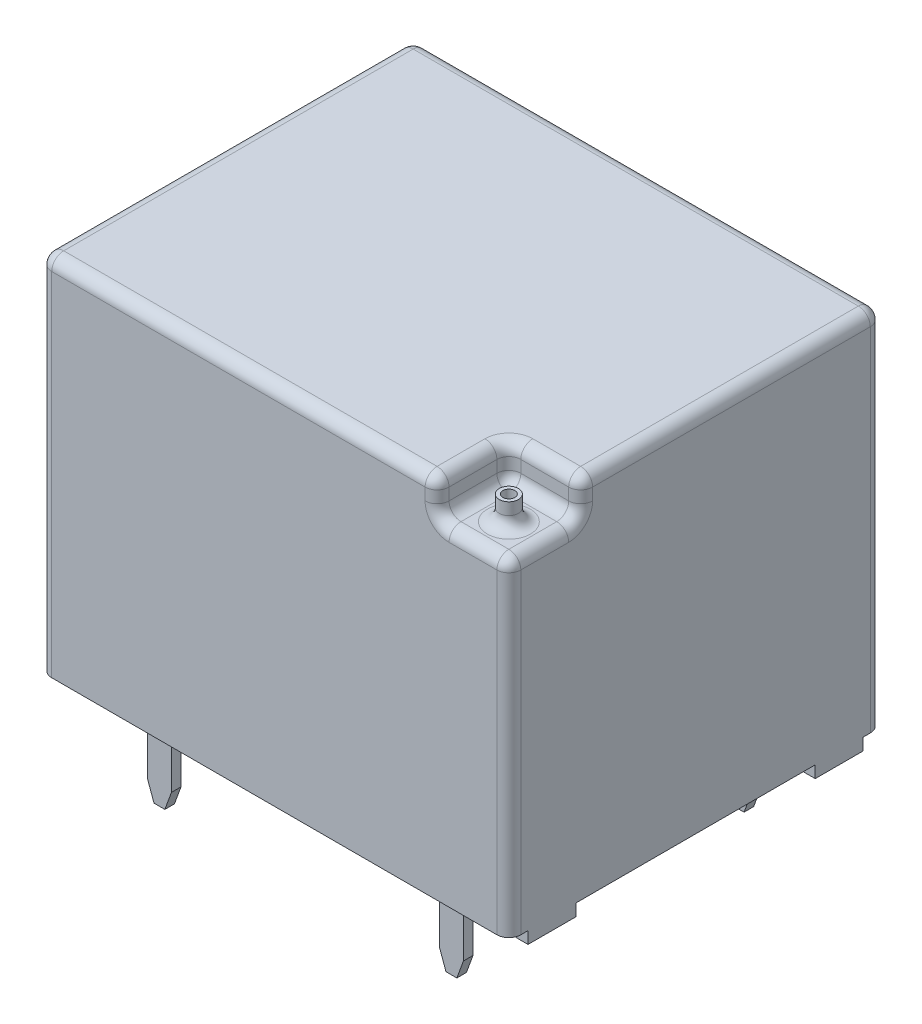
SolidWorks part; units mm, degrees
ref_plane "Спереди" through (0, 0, 0) normal (0, 0, 1) x (1, 0, 0)
ref_plane "Сверху" through (0, 0, 0) normal (0, 1, 0) x (1, 0, 0)
ref_plane "Справа" through (0, 0, 0) normal (1, 0, 0) x (0, 0, -1)
sketch "Эскиз1" plane through (0, 0, 0) normal (0, 1, 0) x (1, 0, 0)
  line L1 (-9.8, -7.8) -> (9.8, -7.8)
  line L2 (-9.8, -7.8) -> (-9.8, 7.8)
  line L3 (-9.8, 7.8) -> (9.8, 7.8)
  line L4 (9.8, -7.8) -> (9.8, 7.8)
  line L5 (-9.8, -7.8) -> (9.8, 7.8) construction
  line L6 (-9.8, 7.8) -> (9.8, -7.8) construction
  point P0 (0, 0)
  dimension "D1" = 19.6
  dimension "D2" = 15.6
extrude "Бобышка-Вытянуть1" add sketch "Эскиз1" along normal blind 15.2
sketch "Эскиз2" plane through (0, 15.2, 0) normal (0, 1, 0) x (1, 0, 0)
  line L0 (9.8, -7.8) -> (9.8, 7.8) construction
  line L1 (9.8, -7.8) -> (6.8, -7.8)
  line L2 (9.8, -7.8) -> (9.8, -4.8)
  line L3 (9.8, -4.8) -> (6.8, -4.8)
  line L4 (6.8, -7.8) -> (6.8, -4.8)
  dimension "D1" = 3
extrude "Вырез-Вытянуть1" cut sketch "Эскиз2" against normal blind 1.5
sketch "Эскиз3" plane through (0, 13.7, 0) normal (0, 1, 0) x (1, 0, 0)
  line L0 (6.8, -7.8) -> (9.8, -7.8) construction
  line L1 (9.8, -7.8) -> (9.8, -4.8) construction
  circle A0 centre (8.3, -6.3) radius 0.4
  circle A1 centre (8.3, -6.3) radius 0.25
  point P3 (8.3, -7.8)
  point P4 (9.8, -6.3)
  dimension "D1" = 0.8
  dimension "D2" = 0.5
extrude "Бобышка-Вытянуть2" add sketch "Эскиз3" along normal blind 1
sketch "Эскиз5" plane through (0, 0, 0) normal (0, -1, 0) x (1, 0, 0)
  line L0 (-12.3482, 0) -> (15.0371, 0) construction
  line L2 (-9.55, -6) -> (-9.55, 6) construction
  line L3 (-9.3, 5) -> (-9.8, 5)
  line L4 (-9.3, 5) -> (-9.3, 7)
  line L5 (-9.3, 7) -> (-9.8, 7)
  line L6 (-9.8, 5) -> (-9.8, 7)
  line L7 (-9.3, 5) -> (-9.8, 7) construction
  line L9 (-9.3, 7) -> (-9.8, 5) construction
  line L10 (-9.3, -7) -> (-9.8, -7)
  line L11 (-9.3, -7) -> (-9.3, -5)
  line L12 (-9.3, -5) -> (-9.8, -5)
  line L13 (-9.8, -7) -> (-9.8, -5)
  line L14 (-9.3, -7) -> (-9.8, -5) construction
  line L15 (-9.3, -5) -> (-9.8, -7) construction
  line L16 (9.8, -7) -> (9.3, -7)
  line L17 (9.8, -7) -> (9.8, -5)
  line L18 (9.8, -5) -> (9.3, -5)
  line L19 (9.3, -7) -> (9.3, -5)
  line L20 (9.8, -7) -> (9.3, -5) construction
  line L21 (9.8, -5) -> (9.3, -7) construction
  line L22 (9.8, 5) -> (9.3, 5)
  line L23 (9.8, 5) -> (9.8, 7)
  line L24 (9.8, 7) -> (9.3, 7)
  line L25 (9.3, 5) -> (9.3, 7)
  line L26 (9.8, 5) -> (9.3, 7) construction
  line L27 (9.8, 7) -> (9.3, 5) construction
  line L28 (-9.8, -7.8) -> (-9.8, 7.8) construction
  line L29 (9.8, 7.8) -> (9.8, -7.8) construction
  point P1 (-9.55, 6)
  point P8 (-9.55, -6)
  point P13 (9.55, -6)
  point P18 (9.55, 6)
  point P26 (-9.55, 0)
  dimension "D1" = 2
  dimension "D2" = 0.5
  dimension "D3" = 12
extrude "Бобышка-Вытянуть4" add sketch "Эскиз5" along normal blind 0.5
fillet "Скругление1" radius 0.5 18 edges at (8.3, 15.2, 4.8) (-9.8, 7.6, -7.8) (-9.8, 15.2, 0) (9.8, 7.6, -7.8) (0, 15.2, -7.8) (9.8, 15.2, -1.5) (8.3, 13.7, 6.7) (6.8, 13.7, 6.3) (8.3, 13.7, 4.8) (9.8, 14.45, 4.8) (8.3, 13.7, 7.8) (9.8, 13.7, 6.3) (6.8, 14.45, 4.8) (6.8, 15.2, 6.3) (6.8, 14.45, 7.8) (-1.5, 15.2, 7.8) (9.8, 6.85, 7.8) (-9.8, 7.6, 7.8)
sketch "Эскиз4" plane through (0, 0, 0) normal (0, -1, 0) x (1, 0, 0)
  line L0 (-11.9961, 0) -> (11.2464, 0) construction
  line L1 (9.8, 7.8) -> (9.8, -7.8) construction
  line L2 (-8.525, -0.6) -> (-8.275, -0.6)
  line L3 (-8.525, -0.6) -> (-8.525, 0.6)
  line L4 (-8.525, 0.6) -> (-8.275, 0.6)
  line L5 (-8.275, -0.6) -> (-8.275, 0.6)
  line L6 (-8.525, -0.6) -> (-8.275, 0.6) construction
  line L7 (-8.525, 0.6) -> (-8.275, -0.6) construction
  line L8 (-6.4, -6) -> (5.8, -6) construction
  line L9 (-6.4, -6) -> (-6.4, 6) construction
  line L10 (-6.4, 6) -> (5.8, 6) construction
  line L11 (5.8, -6) -> (5.8, 6) construction
  line L12 (-6.4, -6) -> (5.8, 6) construction
  line L13 (-6.4, 6) -> (5.8, -6) construction
  line L14 (-5.9, 5.8) -> (-6.9, 5.8)
  line L15 (-5.9, 5.8) -> (-5.9, 6.2)
  line L16 (-5.9, 6.2) -> (-6.9, 6.2)
  line L17 (-6.9, 5.8) -> (-6.9, 6.2)
  line L18 (-5.9, 5.8) -> (-6.9, 6.2) construction
  line L19 (-5.9, 6.2) -> (-6.9, 5.8) construction
  line L20 (6.3, 5.8) -> (5.3, 5.8)
  line L21 (6.3, 5.8) -> (6.3, 6.2)
  line L22 (6.3, 6.2) -> (5.3, 6.2)
  line L23 (5.3, 5.8) -> (5.3, 6.2)
  line L24 (6.3, 5.8) -> (5.3, 6.2) construction
  line L25 (6.3, 6.2) -> (5.3, 5.8) construction
  line L26 (5.3, -5.8) -> (6.3, -5.8)
  line L27 (5.3, -5.8) -> (5.3, -6.2)
  line L28 (5.3, -6.2) -> (6.3, -6.2)
  line L29 (6.3, -5.8) -> (6.3, -6.2)
  line L30 (5.3, -5.8) -> (6.3, -6.2) construction
  line L31 (5.3, -6.2) -> (6.3, -5.8) construction
  line L32 (-6.9, -5.8) -> (-5.9, -5.8)
  line L33 (-6.9, -5.8) -> (-6.9, -6.2)
  line L34 (-6.9, -6.2) -> (-5.9, -6.2)
  line L35 (-5.9, -5.8) -> (-5.9, -6.2)
  line L36 (-6.9, -5.8) -> (-5.9, -6.2) construction
  line L37 (-6.9, -6.2) -> (-5.9, -5.8) construction
  point P3 (-8.4, 0)
  point P8 (-0.3, 0)
  dimension "D1" = 12.2
  dimension "D2" = 12
  dimension "D3" = 2
  dimension "D4" = 4
  dimension "D5" = 0.4
  dimension "D6" = 1
  dimension "D7" = 1.2
  dimension "D8" = 0.25
extrude "Бобышка-Вытянуть3" add sketch "Эскиз4" along normal blind 4
chamfer "Фаска1" distance 0.75 angle 20 10 edges at (-5.9, -4, 6) (-6.9, -4, 6) (6.3, -4, 6) (5.3, -4, 6) (6.3, -4, -6) (5.3, -4, -6) (-5.9, -4, -6) (-6.9, -4, -6) (-8.4, -4, 0.6) (-8.4, -4, -0.6)
